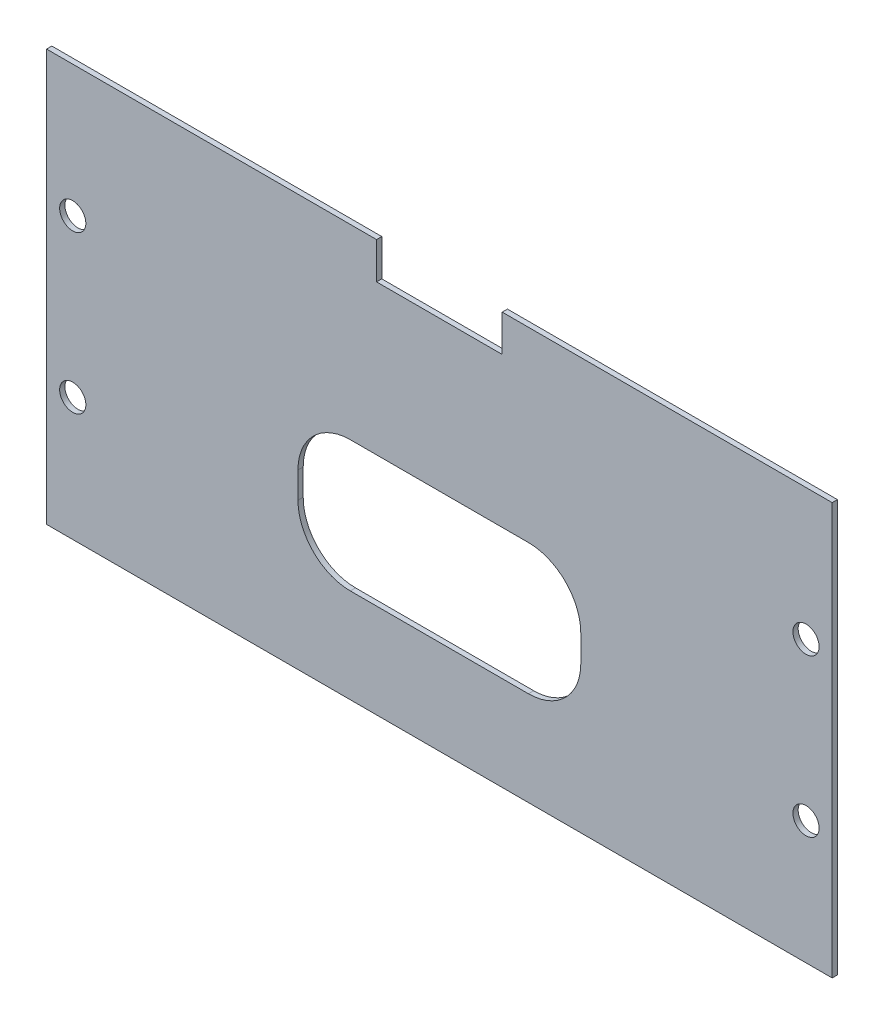
SolidWorks part; units mm, degrees
ref_plane "Front" through (0, 0, 0) normal (0, 0, 1) x (1, 0, 0)
ref_plane "Top" through (0, 0, 0) normal (0, 1, 0) x (1, 0, 0)
ref_plane "Right" through (0, 0, 0) normal (1, 0, 0) x (0, 0, -1)
sketch "Sketch1" plane through (0, 0, 0) normal (0, 0, 1) x (1, 0, 0)
  line L1 (-75, -41.8) -> (75, -41.8)
  line L2 (-75, -41.8) -> (-75, 41.8)
  line L3 (-75, 41.8) -> (75, 41.8)
  line L4 (75, -41.8) -> (75, 41.8)
  line L5 (-75, -41.8) -> (75, 41.8) construction
  line L6 (-75, 41.8) -> (75, -41.8) construction
  point P0 (0, 0)
  dimension "D1" = 83.6
  dimension "D2" = 150
extrude "Boss-Extrude1" add sketch "Sketch1" along normal blind 1
sketch "Sketch2" plane through (0, 0, 1) normal (0, 0, 1) x (1, 0, 0)
  line L1 (-27, 6.2) -> (27, 6.2)
  line L2 (-27, 6.2) -> (-27, -18.8)
  line L3 (-27, -18.8) -> (27, -18.8)
  line L4 (27, 6.2) -> (27, -18.8)
  line L5 (-75, -41.8) -> (75, -41.8) construction
  line L6 (0, 6.2) -> (0, 0) construction
  line L7 (0, 0) -> (0, -41.8) construction
  dimension "D1" = 25
  dimension "D2" = 54
  dimension "D4" = 23
extrude "Cut-Extrude1" cut sketch "Sketch2" against normal through all contours L2 L1 L4 L3
sketch "Sketch3" plane through (0, 0, 1) normal (0, 0, 1) x (1, 0, 0)
  line L0 (-75, -41.8) -> (75, -41.8) construction
  line L1 (-75, 41.8) -> (-75, -41.8) construction
  line L2 (0, 0) -> (0, -41.8)
  circle A0 centre (-70, 16.72) radius 2.5
  circle A1 centre (-70, -13.28) radius 2.5
  circle A2 centre (70, -13.28) radius 2.5
  circle A3 centre (70, 16.72) radius 2.5
  dimension "D1" = 5
  dimension "D2" = 58.52
  dimension "D3" = 28.52
  dimension "D5" = 5
  dimension "D4" = 5
extrude "Cut-Extrude2" cut sketch "Sketch3" against normal blind 6.5 contours A0 | A1 | A3 | A2
sketch "Sketch4" plane through (0, 0, 1) normal (0, 0, 1) x (1, 0, 0)
  line L0 (0, 41.8) -> (0, 34.8) construction
  line L1 (75, 41.8) -> (-75, 41.8) construction
  line L2 (0, 34.8) -> (12, 34.8)
  line L3 (12, 34.8) -> (12, 41.8)
  line L4 (12, 41.8) -> (-12, 41.8)
  line L5 (-12, 41.8) -> (-12, 34.8)
  line L6 (-12, 34.8) -> (0, 34.8)
  dimension "D1" = 7
  dimension "D2" = 24
  dimension "D3" = 12
extrude "Cut-Extrude3" cut sketch "Sketch4" against normal blind 10
fillet "Fillet1" radius 10 4 edges at (27, -18.8, 0.5) (27, 6.2, 0.5) (-27, 6.2, 0.5) (-27, -18.8, 0.5)
sketch "Sketch5" plane through (0, 0, 1) normal (0, 0, 1) x (1, 0, 0)
  line L0 (-75, -41.8) -> (-75, -36.8)
  line L1 (-75, 41.8) -> (-75, -41.8) construction
  line L2 (-75, -36.8) -> (75, -36.8)
  line L3 (75, -41.8) -> (75, 41.8) construction
  line L4 (75, -36.8) -> (75, -41.8)
  line L5 (75, -41.8) -> (-75, -41.8)
  dimension "D1" = 5
extrude "Cut-Extrude4" cut sketch "Sketch5" against normal blind 10
